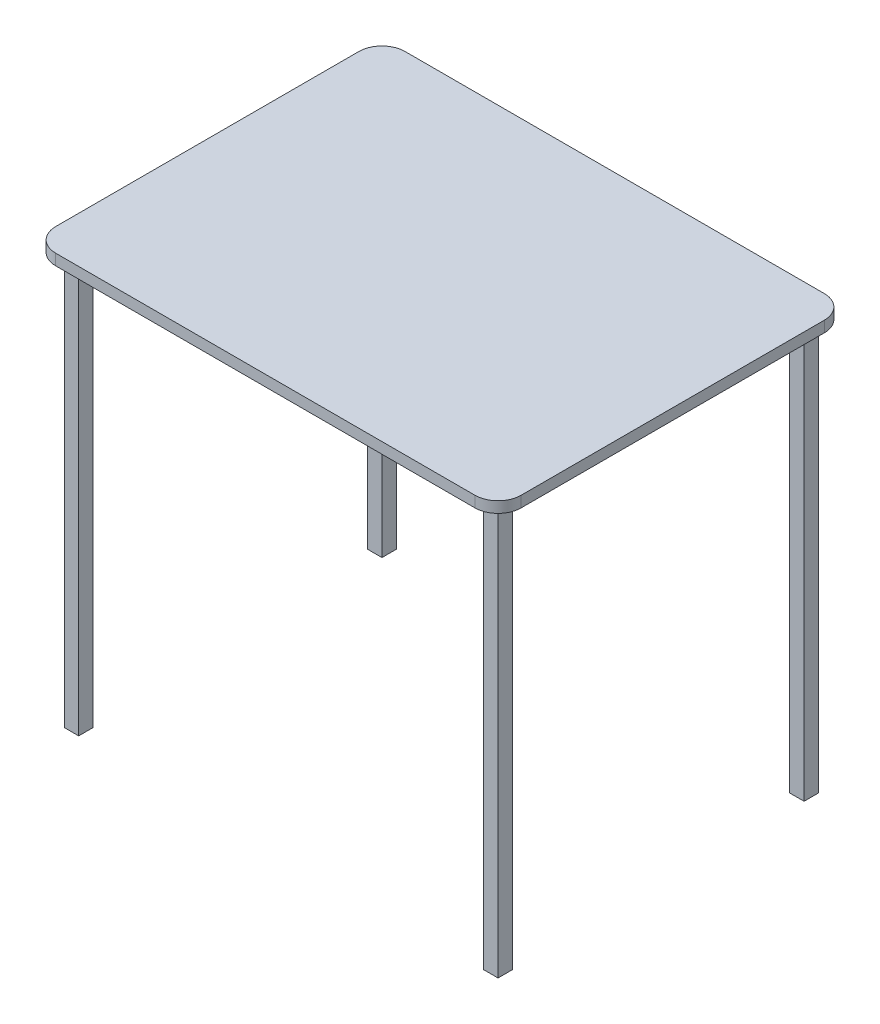
SolidWorks part; units mm, degrees
ref_plane "Front Plane" through (0, 0, 0) normal (0, 0, 1) x (1, 0, 0)
ref_plane "Top Plane" through (0, 0, 0) normal (0, 1, 0) x (1, 0, 0)
ref_plane "Right Plane" through (0, 0, 0) normal (1, 0, 0) x (0, 0, -1)
sketch "Sketch2" plane through (0, 0, 0) normal (0, 1, 0) x (1, 0, 0)
  line L1 (-403, -302.5) -> (403, -302.5)
  line L2 (-403, -302.5) -> (-403, 302.5)
  line L3 (-403, 302.5) -> (403, 302.5)
  line L4 (403, -302.5) -> (403, 302.5)
  line L5 (-403, -302.5) -> (403, 302.5) construction
  line L6 (-403, 302.5) -> (403, -302.5) construction
  point P0 (0, 0)
  dimension "D1" = 605
  dimension "D2" = 806
extrude "Boss-Extrude1" add sketch "Sketch2" along normal blind 19 contours L2 L1 L4 L3
sketch "Sketch4" plane through (0, 0, 0) normal (0, -1, 0) x (1, 0, 0)
  line L0 (-373.1786, 302.5) -> (-373.1786, 277.5)
  line L5 (-403, 302.5) -> (403, 302.5) construction
  line L6 (-403, -302.5) -> (-403, -277.5)
  line L7 (-403, 302.5) -> (-403, -302.5) construction
  line L8 (-403, -277.5) -> (-378, -277.5)
  line L13 (403, -277.5) -> (378, -277.5)
  line L14 (403, 302.5) -> (403, -302.5) construction
  line L15 (370.4959, -302.5) -> (370.4959, -277.5)
  line L16 (-403, -302.5) -> (403, -302.5) construction
  line L17 (378, 302.5) -> (378, 277.5)
  line L18 (378, 277.5) -> (403, 277.5)
  line L20 (-373.1786, 277.5) -> (-348.1786, 277.5)
  line L21 (-373.1786, 277.5) -> (-373.1786, 252.5)
  line L22 (-373.1786, 252.5) -> (-348.1786, 252.5)
  line L23 (-348.1786, 277.5) -> (-348.1786, 252.5)
  line L24 (378, 277.5) -> (353, 277.5)
  line L25 (378, 277.5) -> (378, 252.5)
  line L26 (378, 252.5) -> (353, 252.5)
  line L27 (353, 277.5) -> (353, 252.5)
  line L28 (378, -277.5) -> (353, -277.5)
  line L29 (378, -277.5) -> (378, -252.5)
  line L30 (378, -252.5) -> (353, -252.5)
  line L31 (353, -277.5) -> (353, -252.5)
  line L32 (-378, -277.5) -> (-353, -277.5)
  line L33 (-378, -277.5) -> (-378, -252.5)
  line L34 (-378, -252.5) -> (-353, -252.5)
  line L35 (-353, -277.5) -> (-353, -252.5)
  point P33 (0, 0)
  dimension "D1" = 25
  dimension "D2" = 25
  dimension "D3" = 25
  dimension "D4" = 25
  dimension "D5" = 25
  dimension "D6" = 25
  dimension "D7" = 25
  dimension "D8" = 25
  dimension "D9" = 25
  dimension "D10" = 25
  dimension "D11" = 25
  dimension "D12" = 25
  dimension "D13" = 25
extrude "Boss-Extrude3" add sketch "Sketch4" along normal blind 710 contours L25 L26 L27 L24 | L21 L22 L23 L20 | L28 L31 L30 L29 | L32 L35 L34 L33
fillet "Fillet2" radius 40 1 edges at (403, 9.5, 302.5)
fillet "Fillet3" radius 40 1 edges at (-403, 9.5, 302.5)
fillet "Fillet4" radius 40 2 edges at (-403, 9.5, -302.5) (403, 9.5, -302.5)
